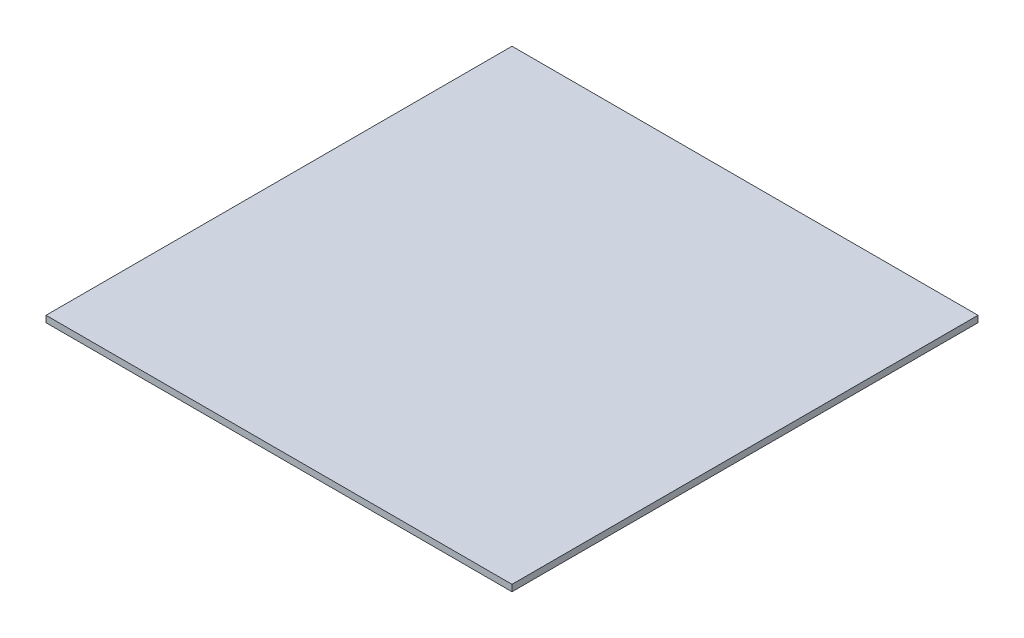
SolidWorks part; units mm, degrees
ref_plane "Front Plane" through (0, 0, 0) normal (0, 0, 1) x (1, 0, 0)
ref_plane "Top Plane" through (0, 0, 0) normal (0, 1, 0) x (1, 0, 0)
ref_plane "Right Plane" through (0, 0, 0) normal (1, 0, 0) x (0, 0, -1)
sketch "Sketch1" plane through (0, 0, 0) normal (0, 1, 0) x (1, 0, 0)
  line L0 (0, 914.4) -> (0, -914.4) construction
  line L1 (-914.4, 914.4) -> (914.4, 914.4)
  line L2 (-914.4, 914.4) -> (-914.4, -914.4)
  line L3 (-914.4, -914.4) -> (914.4, -914.4)
  line L4 (914.4, 914.4) -> (914.4, -914.4)
  dimension "D1" = 1828.8
  dimension "D2" = 1828.8
extrude "Boss-Extrude1" add sketch "Sketch1" against normal blind 25.4
